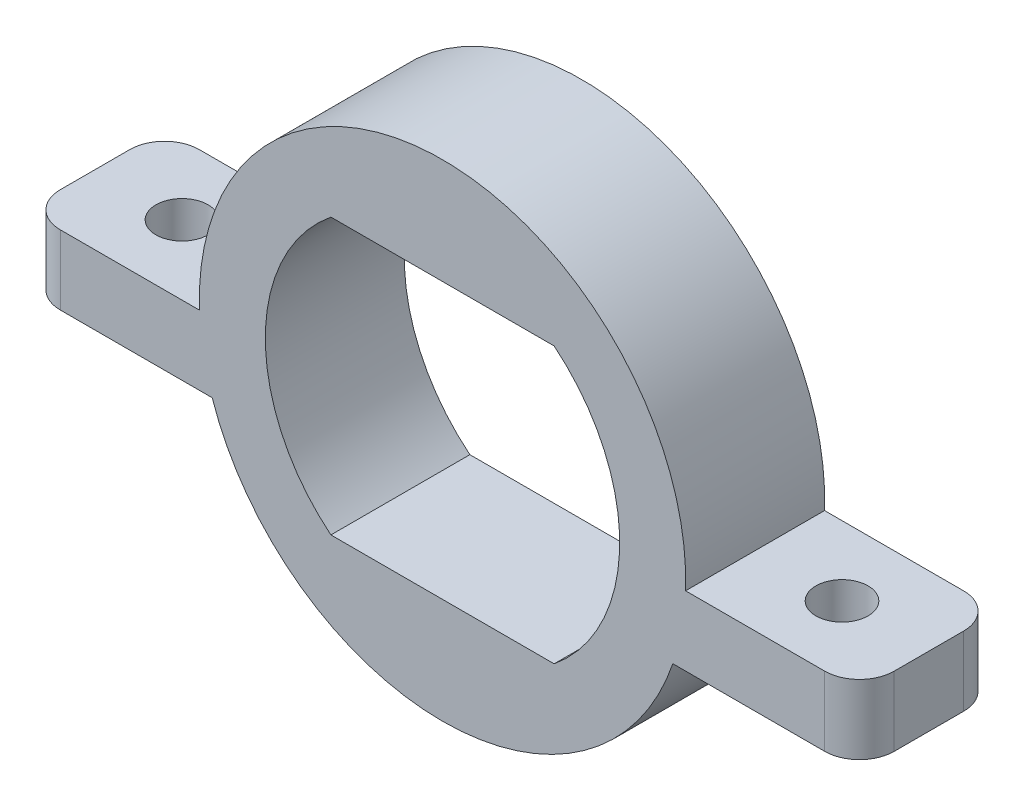
SolidWorks part; units mm, degrees
ref_plane "Alzado" through (0, 0, 0) normal (0, 0, 1) x (1, 0, 0)
ref_plane "Planta" through (0, 0, 0) normal (0, 1, 0) x (1, 0, 0)
ref_plane "Vista lateral" through (0, 0, 0) normal (1, 0, 0) x (0, 0, -1)
sketch "Croquis1" plane through (0, 0, 0) normal (0, 0, 1) x (1, 0, 0)
  line L0 (-12, 0) -> (-24, 0) construction
  line L1 (-24, 0) -> (-24, -0.5) construction
  line L2 (-24, -0.5) -> (-13.9911, -0.5)
  line L3 (-24, -0.5) -> (-24, -4.5)
  line L4 (-24, -4.5) -> (-13.2571, -4.5)
  line L5 (0, -10) -> (0, 10) construction
  line L6 (24, -4.5) -> (13.2571, -4.5)
  line L7 (24, -0.5) -> (24, -4.5)
  line L8 (24, -0.5) -> (13.9911, -0.5)
  line L9 (-24, -4.5) -> (-24, -12.5) construction
  line L10 (0, 0) -> (0, -17.5) construction
  circle A0 centre (0, 0) radius 10
  arc A1 (13.9911, -0.5) -> (-13.9911, -0.5) centre (0, 0) ccw
  arc A2 (-13.2571, -4.5) -> (13.2571, -4.5) centre (0, 0) ccw
  dimension "D1" = 20
  dimension "D2" = 0.5
  dimension "D5" = 4
  dimension "D6" = 24
  dimension "D4" = 4
  dimension "D3" = 4
extrude "Saliente-Extruir1" add sketch "Croquis1" along normal blind 8 contours A1 L2 L3 L4 A2 L6 L7 L8
sketch "Croquis2" plane through (0, 0, 8) normal (0, 0, 1) x (1, 0, 0)
  line L0 (-6.425, 7.9221) -> (6.425, 7.9221)
  line L1 (-6.425, -7.9221) -> (6.425, -7.9221)
  arc A0 (-6.425, 7.9221) -> (-6.425, -7.9221) centre (0, 0) ccw
  arc A1 (6.425, 7.9221) -> (6.425, -7.9221) centre (0, 0) cw
  dimension "D1" = 15.8442
  dimension "D2" = 10.2
  dimension "D3" = 7.9221
extrude "Cortar-Extruir1" cut sketch "Croquis2" against normal through all
sketch "Croquis3" plane through (0, -0.5, 0) normal (0, 1, 0) x (1, 0, 0)
  line L0 (24, 0) -> (13.9911, -8) construction
  line L1 (-13.9911, 0) -> (-24, -8) construction
  circle A0 centre (18.9955, -4) radius 1.5
  circle A1 centre (-18.9955, -4) radius 1.5
  dimension "D1" = 3
  dimension "D2" = 3
extrude "Cortar-Extruir2" cut sketch "Croquis3" against normal blind 5
fillet "Redondeo1" radius 2 4 edges at (24, -2.5, 8) (24, -2.5, 0) (-24, -2.5, 0) (-24, -2.5, 8)
